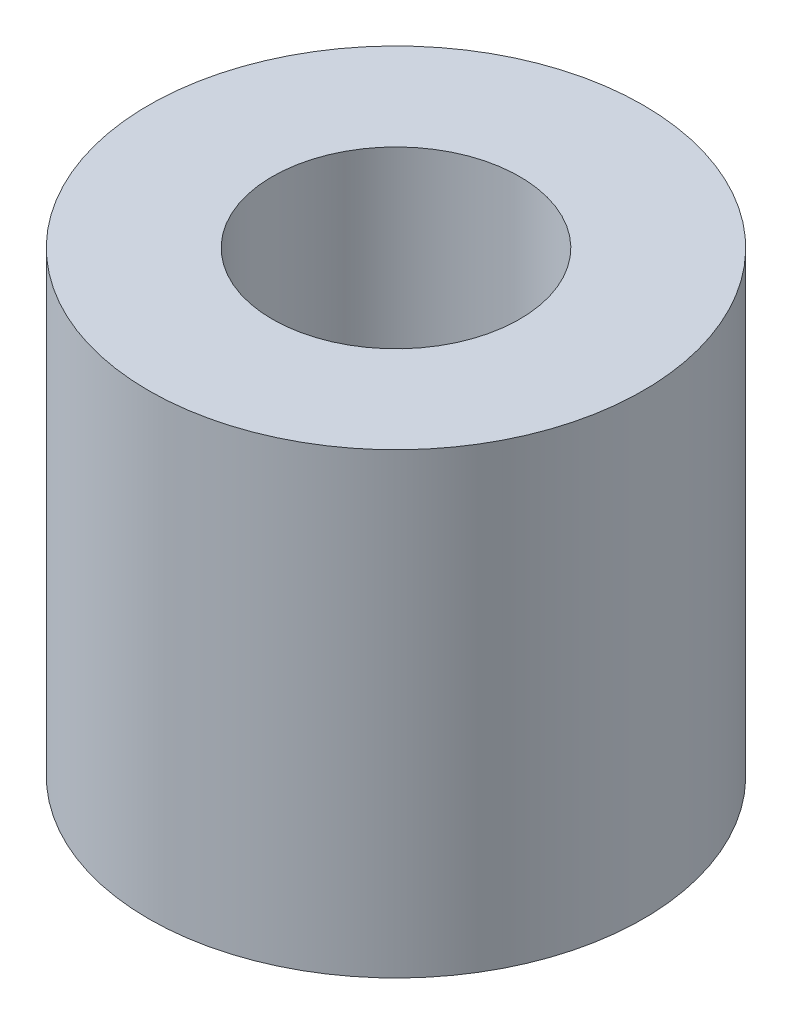
SolidWorks part; units mm, degrees
ref_plane "Front Plane" through (0, 0, 0) normal (0, 0, 1) x (1, 0, 0)
ref_plane "Top Plane" through (0, 0, 0) normal (0, 1, 0) x (1, 0, 0)
ref_plane "Right Plane" through (0, 0, 0) normal (1, 0, 0) x (0, 0, -1)
sketch "Sketch1" plane through (0, 0, 0) normal (0, 1, 0) x (1, 0, 0)
  circle A0 centre (0, 0) radius 2.54
  circle A1 centre (0, 0) radius 5.08
  dimension "D1" = 5.08
  dimension "D2" = 10.16
extrude "Boss-Extrude1" add sketch "Sketch1" along normal blind 9.398
